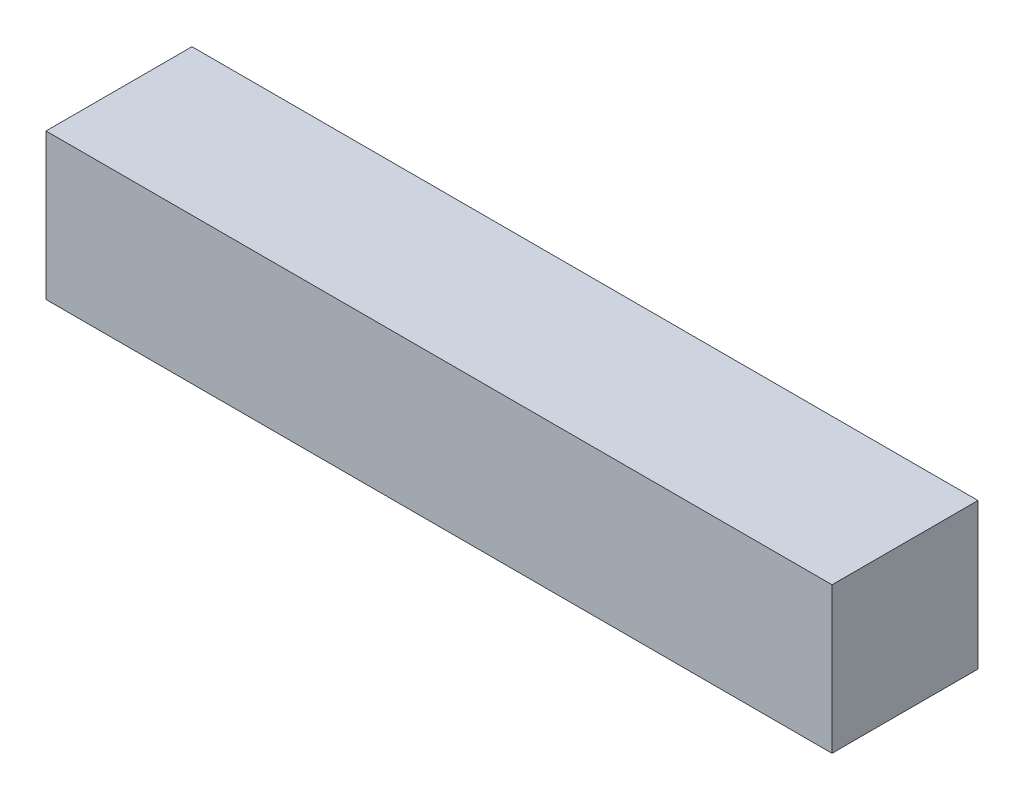
SolidWorks part; units mm, degrees
ref_plane "Front Plane" through (0, 0, 0) normal (0, 0, 1) x (1, 0, 0)
ref_plane "Top Plane" through (0, 0, 0) normal (0, 1, 0) x (1, 0, 0)
ref_plane "Right Plane" through (0, 0, 0) normal (1, 0, 0) x (0, 0, -1)
sketch "Sketch1" plane through (0, 0, 0) normal (0, 0, 1) x (1, 0, 0)
  line L1 (-7, 1.3) -> (7, 1.3)
  line L2 (-7, 1.3) -> (-7, -1.3)
  line L3 (-7, -1.3) -> (7, -1.3)
  line L4 (7, 1.3) -> (7, -1.3)
  line L5 (-7, 1.3) -> (7, -1.3) construction
  line L6 (-7, -1.3) -> (7, 1.3) construction
  point P0 (0, 0)
  dimension "D1" = 14
  dimension "D2" = 2.6
extrude "Boss-Extrude1" add sketch "Sketch1" along normal blind 2.6
equation "\"D1@Boss-Extrude1\"=\"D2@Sketch1\""
